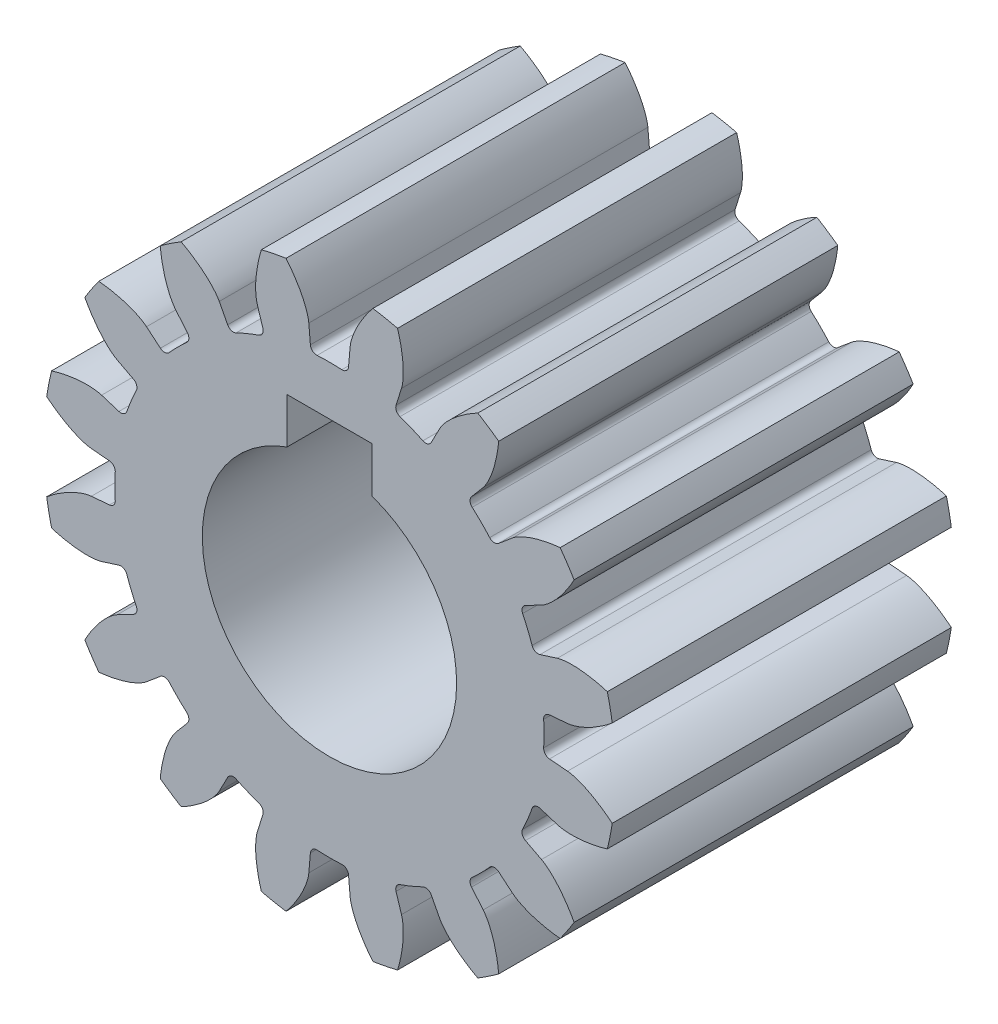
SolidWorks part; units mm, degrees
ref_plane "中间平面" through (0, 0, 0) normal (0, 0, 1) x (1, 0, 0)
ref_plane "上视基准面" through (0, 0, 0) normal (0, 1, 0) x (1, 0, 0)
ref_plane "右视基准面" through (0, 0, 0) normal (1, 0, 0) x (0, 0, -1)
sketch "直齿轮" plane through (0, 0, 0) normal (0, 0, 1) x (1, 0, 0)
  line L0 (0, 0) -> (-1.1762, 11.9422) construction
  line L2 (-0.9741, 11.2342) -> (0, 0)
  line L3 (0, 0) -> (0, 52) construction
  line L4 (1.1762, 11.9422) -> (0, 0) construction
  line L6 (0, 0) -> (0.9741, 11.2342)
  circle A0 centre (0, 0) radius 11.2763
  circle A1 centre (0, 0) radius 10.125
  arc A2 (1.1762, 11.9422) -> (-1.1762, 11.9422) centre (0, 0) ccw
  circle A3 centre (0, 0) radius 13.5
  spline S0 degree 4 poles (-0.9741, 11.2342) (-0.9778, 11.2769) (-0.9892, 11.3619) (-1.0253, 11.5213) (-1.0968, 11.7512) (-1.2514, 12.1375) (-1.5651, 12.7202) (-2.0889, 13.4422) (-2.9579, 14.3355) (-4.1214, 15.2186) (-5.5257, 15.9949) (-7.1395, 16.6146) (-8.8166, 17.0298) (-10.5294, 17.2529) (-12.3409, 17.2979) (-14.5779, 17.1195) (-17.2003, 16.566) (-20.1221, 15.4847) (-23.1427, 13.7966) (-25.8881, 11.6927) (-28.3234, 9.2384) (-30.1625, 6.8373) (-31.5207, 4.6329) (-32.5047, 2.7147) (-33.2024, 1.1373) (-33.8103, -0.4764) (-34.3283, -2.122) (-34.8638, -4.2093) (-35.2505, -6.3331) (-35.4664, -8.2594) (-35.5513, -9.8775) (-35.5719, -10.733) (-35.5755, -11.3167) (-35.5737, -11.7731) (-35.5588, -12.4198) (-35.5403, -12.9018) (-35.4983, -13.6946) (-35.4489, -14.3031) (-35.381, -15.0475) (-35.3029, -15.7061) (-35.2097, -16.417) (-35.1048, -17.0883) (-35.0154, -17.6149) (-34.9522, -17.9493) (-34.9192, -18.1231) knots 0 0 0 0 0 0.002802 0.005604 0.010661 0.015718 0.02996 0.048734 0.068727 0.096889 0.125051 0.153212 0.181374 0.209535 0.237696 0.271429 0.327752 0.384075 0.440398 0.496721 0.553044 0.609367 0.637529 0.66569 0.693852 0.722013 0.750174 0.778336 0.834659 0.86282 0.876901 0.883942 0.890982 0.900036 0.909091 0.920455 0.931818 0.943182 0.954545 0.965909 0.977273 0.988636 1 1 1 1 1 construction
  spline S1 degree 4 poles (-0.9741, 11.2342) (-0.9778, 11.2769) (-0.9892, 11.3619) (-1.0253, 11.5213) (-1.0968, 11.7512) (-1.2514, 12.1375) (-1.5651, 12.7202) (-2.0889, 13.4422) (-2.9579, 14.3355) (-4.1214, 15.2186) (-5.5257, 15.9949) (-7.1395, 16.6146) (-8.8166, 17.0298) (-10.5294, 17.2529) (-12.3409, 17.2979) (-14.5779, 17.1195) (-17.2003, 16.566) (-20.1221, 15.4847) (-23.1427, 13.7966) (-25.8881, 11.6927) (-28.3234, 9.2384) (-30.1625, 6.8373) (-31.5207, 4.6329) (-32.5047, 2.7147) (-33.2024, 1.1373) (-33.8103, -0.4764) (-34.3283, -2.122) (-34.8638, -4.2093) (-35.2505, -6.3331) (-35.4664, -8.2594) (-35.5513, -9.8775) (-35.5719, -10.733) (-35.5755, -11.3167) (-35.5737, -11.7731) (-35.5634, -12.2185) (-35.5555, -12.4735) (-35.5509, -12.5994) knots 0 0 0 0 0 0.002802 0.005604 0.010661 0.015718 0.02996 0.048734 0.068727 0.096889 0.125051 0.153212 0.181374 0.209535 0.237696 0.271429 0.327752 0.384075 0.440398 0.496721 0.553044 0.609367 0.637529 0.66569 0.693852 0.722013 0.750174 0.778336 0.834659 0.86282 0.876901 0.883942 0.890982 0.900036 0.909091 0.909091 0.909091 0.909091 0.909091
  spline S2 degree 4 poles (0.9741, 11.2342) (0.9778, 11.2769) (0.9892, 11.3619) (1.0253, 11.5213) (1.0968, 11.7512) (1.2514, 12.1375) (1.5651, 12.7202) (2.0889, 13.4422) (2.9579, 14.3355) (4.1214, 15.2186) (5.5257, 15.9949) (7.1395, 16.6146) (8.8166, 17.0298) (10.5294, 17.2529) (12.3409, 17.2979) (14.5779, 17.1195) (17.2003, 16.566) (20.1221, 15.4847) (23.1427, 13.7966) (25.8881, 11.6927) (28.3234, 9.2384) (30.1625, 6.8373) (31.5207, 4.6329) (32.5047, 2.7147) (33.2024, 1.1373) (33.8103, -0.4764) (34.3283, -2.122) (34.8638, -4.2093) (35.2505, -6.3331) (35.4664, -8.2594) (35.5513, -9.8775) (35.5719, -10.733) (35.5755, -11.3167) (35.5737, -11.7731) (35.5588, -12.4198) (35.5403, -12.9018) (35.4983, -13.6946) (35.4489, -14.3031) (35.381, -15.0475) (35.3029, -15.7061) (35.2097, -16.417) (35.1048, -17.0883) (35.0154, -17.6149) (34.9522, -17.9493) (34.9192, -18.1231) knots 0 0 0 0 0 0.002802 0.005604 0.010661 0.015718 0.02996 0.048734 0.068727 0.096889 0.125051 0.153212 0.181374 0.209535 0.237696 0.271429 0.327752 0.384075 0.440398 0.496721 0.553044 0.609367 0.637529 0.66569 0.693852 0.722013 0.750174 0.778336 0.834659 0.86282 0.876901 0.883942 0.890982 0.900036 0.909091 0.920455 0.931818 0.943182 0.954545 0.965909 0.977273 0.988636 1 1 1 1 1 construction
  spline S3 degree 4 poles (0.9741, 11.2342) (0.9778, 11.2769) (0.9892, 11.3619) (1.0253, 11.5213) (1.0968, 11.7512) (1.2514, 12.1375) (1.5651, 12.7202) (2.0889, 13.4422) (2.9579, 14.3355) (4.1214, 15.2186) (5.5257, 15.9949) (7.1395, 16.6146) (8.8166, 17.0298) (10.5294, 17.2529) (12.3409, 17.2979) (14.5779, 17.1195) (17.2003, 16.566) (20.1221, 15.4847) (23.1427, 13.7966) (25.8881, 11.6927) (28.3234, 9.2384) (30.1625, 6.8373) (31.5207, 4.6329) (32.5047, 2.7147) (33.2024, 1.1373) (33.8103, -0.4764) (34.3283, -2.122) (34.8638, -4.2093) (35.2505, -6.3331) (35.4664, -8.2594) (35.5513, -9.8775) (35.5719, -10.733) (35.5755, -11.3167) (35.5737, -11.7731) (35.5634, -12.2185) (35.5555, -12.4735) (35.5509, -12.5994) knots 0 0 0 0 0 0.002802 0.005604 0.010661 0.015718 0.02996 0.048734 0.068727 0.096889 0.125051 0.153212 0.181374 0.209535 0.237696 0.271429 0.327752 0.384075 0.440398 0.496721 0.553044 0.609367 0.637529 0.66569 0.693852 0.722013 0.750174 0.778336 0.834659 0.86282 0.876901 0.883942 0.890982 0.900036 0.909091 0.909091 0.909091 0.909091 0.909091
  dimension "基圆直径" = 22.5526
  dimension "齿根圆" = 20.25
  dimension "分度圆" = 24
  dimension "齿顶圆" = 27
  dimension "D1" = 2.3562
sketch "圆" plane through (0, 0, 0) normal (0, 0, 1) x (1, 0, 0)
  circle A0 centre (0, 0) radius 13.5 construction
  circle A1 centre (0, 0) radius 13.5
extrude "毛胚" add sketch "圆" along normal mid plane 16
chamfer "轮齿倒角" [suppressed] distance 0.001 angle 45
sketch "齿形" plane through (0, 0, 0) normal (0, 0, 1) x (1, 0, 0)
  line L4 (0, 0) -> (0.9741, 11.2342) construction
  line L5 (-0.9741, 11.2342) -> (0, 0) construction
  line L6 (0, 0) -> (0.9741, 11.2342)
  line L7 (-0.9741, 11.2342) -> (0, 0)
  circle A4 centre (0, 0) radius 10.125 construction
  circle A5 centre (0, 0) radius 13.5 construction
  circle A6 centre (0, 0) radius 10.125
  circle A7 centre (0, 0) radius 13.5
  spline S1 degree 4 poles (-998.5818, 40.6491) (42.2018, 3.5521) (1.6144, 7.6088) (0.5146, 9.8809) (1.0968, 11.7512) (1.2514, 12.1375) (1.5651, 12.7202) (2.0889, 13.4422) (2.9579, 14.3355) (4.1214, 15.2186) (5.5257, 15.9949) (7.1395, 16.6146) (8.8166, 17.0298) (10.5294, 17.2529) (12.3409, 17.2979) (14.5779, 17.1195) (17.2003, 16.566) (20.1221, 15.4847) (23.1427, 13.7966) (25.8881, 11.6927) (28.3234, 9.2384) (30.1625, 6.8373) (31.5207, 4.6329) (32.5047, 2.7147) (33.2024, 1.1373) (33.8103, -0.4764) (34.3283, -2.122) (34.8638, -4.2093) (35.2505, -6.3331) (35.4664, -8.2594) (35.5513, -9.8775) (35.5719, -10.733) (35.5755, -11.3167) (35.5671, -13.461) (35.2674, -18.4262) (36.5025, 22.7753) (-1.7629, -1011.8825) knots -0.112202 -0.112202 -0.112202 -0.112202 -0.112202 0.002802 0.005604 0.010661 0.015718 0.02996 0.048734 0.068727 0.096889 0.125051 0.153212 0.181374 0.209535 0.237696 0.271429 0.327752 0.384075 0.440398 0.496721 0.553044 0.609367 0.637529 0.66569 0.693852 0.722013 0.750174 0.778336 0.834659 0.86282 0.876901 0.883942 0.890982 0.900036 1.028138 1.028138 1.028138 1.028138 1.028138 only from (0.9741, 11.2342) to (35.5509, -12.5994) construction
  spline S3 degree 4 poles (998.5818, 40.6491) (-42.2018, 3.5521) (-1.6144, 7.6088) (-0.5146, 9.8809) (-1.0968, 11.7512) (-1.2514, 12.1375) (-1.5651, 12.7202) (-2.0889, 13.4422) (-2.9579, 14.3355) (-4.1214, 15.2186) (-5.5257, 15.9949) (-7.1395, 16.6146) (-8.8166, 17.0298) (-10.5294, 17.2529) (-12.3409, 17.2979) (-14.5779, 17.1195) (-17.2003, 16.566) (-20.1221, 15.4847) (-23.1427, 13.7966) (-25.8881, 11.6927) (-28.3234, 9.2384) (-30.1625, 6.8373) (-31.5207, 4.6329) (-32.5047, 2.7147) (-33.2024, 1.1373) (-33.8103, -0.4764) (-34.3283, -2.122) (-34.8638, -4.2093) (-35.2505, -6.3331) (-35.4664, -8.2594) (-35.5513, -9.8775) (-35.5719, -10.733) (-35.5755, -11.3167) (-35.5671, -13.461) (-35.2674, -18.4262) (-36.5025, 22.7753) (1.7629, -1011.8825) knots -0.112202 -0.112202 -0.112202 -0.112202 -0.112202 0.002802 0.005604 0.010661 0.015718 0.02996 0.048734 0.068727 0.096889 0.125051 0.153212 0.181374 0.209535 0.237696 0.271429 0.327752 0.384075 0.440398 0.496721 0.553044 0.609367 0.637529 0.66569 0.693852 0.722013 0.750174 0.778336 0.834659 0.86282 0.876901 0.883942 0.890982 0.900036 1.028138 1.028138 1.028138 1.028138 1.028138 only from (-0.9741, 11.2342) to (-35.5509, -12.5994) construction
  spline S4 degree 4 poles (0.9741, 11.2342) (0.9778, 11.2769) (0.9892, 11.3619) (1.0253, 11.5213) (1.0968, 11.7512) (1.2514, 12.1375) (1.5651, 12.7202) (2.0889, 13.4422) (2.9579, 14.3355) (4.1214, 15.2186) (5.5257, 15.9949) (7.1395, 16.6146) (8.8166, 17.0298) (10.5294, 17.2529) (12.3409, 17.2979) (14.5779, 17.1195) (17.2003, 16.566) (20.1221, 15.4847) (23.1427, 13.7966) (25.8881, 11.6927) (28.3234, 9.2384) (30.1625, 6.8373) (31.5207, 4.6329) (32.5047, 2.7147) (33.2024, 1.1373) (33.8103, -0.4764) (34.3283, -2.122) (34.8638, -4.2093) (35.2505, -6.3331) (35.4664, -8.2594) (35.5513, -9.8775) (35.5719, -10.733) (35.5755, -11.3167) (35.5737, -11.7731) (35.5634, -12.2185) (35.5555, -12.4735) (35.5509, -12.5994) knots 0 0 0 0 0 0.002802 0.005604 0.010661 0.015718 0.02996 0.048734 0.068727 0.096889 0.125051 0.153212 0.181374 0.209535 0.237696 0.271429 0.327752 0.384075 0.440398 0.496721 0.553044 0.609367 0.637529 0.66569 0.693852 0.722013 0.750174 0.778336 0.834659 0.86282 0.876901 0.883942 0.890982 0.900036 0.909091 0.909091 0.909091 0.909091 0.909091
  spline S5 degree 4 poles (-0.9741, 11.2342) (-0.9778, 11.2769) (-0.9892, 11.3619) (-1.0253, 11.5213) (-1.0968, 11.7512) (-1.2514, 12.1375) (-1.5651, 12.7202) (-2.0889, 13.4422) (-2.9579, 14.3355) (-4.1214, 15.2186) (-5.5257, 15.9949) (-7.1395, 16.6146) (-8.8166, 17.0298) (-10.5294, 17.2529) (-12.3409, 17.2979) (-14.5779, 17.1195) (-17.2003, 16.566) (-20.1221, 15.4847) (-23.1427, 13.7966) (-25.8881, 11.6927) (-28.3234, 9.2384) (-30.1625, 6.8373) (-31.5207, 4.6329) (-32.5047, 2.7147) (-33.2024, 1.1373) (-33.8103, -0.4764) (-34.3283, -2.122) (-34.8638, -4.2093) (-35.2505, -6.3331) (-35.4664, -8.2594) (-35.5513, -9.8775) (-35.5719, -10.733) (-35.5755, -11.3167) (-35.5737, -11.7731) (-35.5634, -12.2185) (-35.5555, -12.4735) (-35.5509, -12.5994) knots 0 0 0 0 0 0.002802 0.005604 0.010661 0.015718 0.02996 0.048734 0.068727 0.096889 0.125051 0.153212 0.181374 0.209535 0.237696 0.271429 0.327752 0.384075 0.440398 0.496721 0.553044 0.609367 0.637529 0.66569 0.693852 0.722013 0.750174 0.778336 0.834659 0.86282 0.876901 0.883942 0.890982 0.900036 0.909091 0.909091 0.909091 0.909091 0.909091
extrude "插齿" cut sketch "齿形" against normal mid plane 16 contours S5 A6 S4 A7
fillet "圆角1" [suppressed] radius 0.3
pattern_circular "圆周阵列1" [suppressed] count 16 over 360
fillet "圆角2" radius 0.3 2 edges at (0.8747, 10.0871, 0) (-0.8747, 10.0871, 0)
pattern_circular "圆周阵列2" count 16 over 360 about axis through (0, 0, 8) along (0, 0, -1) of "圆角2", "插齿"
sketch "分度圆" plane through (0, 0, 0) normal (0, 0, 1) x (1, 0, 0)
  circle A0 centre (0, 0) radius 12 construction
  circle A1 centre (0, 0) radius 12 construction
sketch "草图1" plane through (0, 0, 8) normal (0, 0, 1) x (1, 0, 0)
  line L0 (0, 6) -> (2, 4.2) construction
  line L1 (-2, 4.2) -> (2, 4.2) construction
  line L2 (-2, 5.6569) -> (-2, 7.8)
  line L3 (-2, 7.8) -> (2, 7.8)
  line L4 (2, 5.6569) -> (2, 7.8)
  line L5 (0, 6) -> (2, 7.8) construction
  line L6 (-2, 7.8) -> (0, 6) construction
  line L7 (2, 4.2) -> (2, 5.6569) construction
  line L8 (-2, 4.2) -> (0, 6) construction
  line L9 (-2, 4.2) -> (-2, 5.6569) construction
  arc A0 (-2, 5.6569) -> (2, 5.6569) centre (0, 0) ccw
  arc A1 (2, 5.6569) -> (0, 6) centre (0, 0) ccw construction
  arc A2 (0, 6) -> (-2, 5.6569) centre (0, 0) ccw construction
  point P3 (0, 6)
  dimension "D1" = 12
  dimension "D2" = 13.8
  dimension "D3" = 4
extrude "切除-拉伸1" cut sketch "草图1" against normal through all both and the other way through all
equation "\"m\" = 1.5'模数"
equation "\"z\" = 16'齿数"
equation "\"a\" = 20'压力角（常见为20°）"
equation "\"B\"= 16'齿宽"
equation "\"C1\" = 0'轮齿倒角（若设为0，则无倒角）"
equation "\"x\"= 0'变位系数（不懂勿动）"
equation "\"ha\"= 1'齿顶高系数（不懂勿动）"
equation "\"c\"= 0.25'顶隙系数（不懂勿动）"
equation "\"基圆直径@直齿轮\"= \"m\" * \"z\" * cos ( \"a\" )"
equation "\"齿根圆@直齿轮\" = \"m\" * ( \"z\" - 2 * ( \"ha\" - \"x\" + \"c\" ) )"
equation "\"分度圆@直齿轮\"=\"m\" * \"z\""
equation "\"齿顶圆@直齿轮\" = \"m\" * ( \"z\" + 2 * ( \"ha\" + \"x\" ) )"
equation "\"R\"= 0.3'齿根圆角"
equation "\"D1\"= \"R\""
equation "\"D1@毛胚\" = \"B\""
equation "\"D1@轮齿倒角\" = IIF ( \"C1\" > 0 , \"C1\" , 0.001 )"
equation "\"轮齿倒角\"= IIF ( \"C1\" > 0 , \"unsuppressed\" , \"suppressed\" )"
equation "\"D1@插齿\" = \"B\""
equation "\"D1@圆周阵列1\" = \"z\""
equation "\"D1@直齿轮\"= \"m\" * ( pi / 2 ) - 2 * \"m\" * tan ( \"a\" ) * \"x\"'作者：机械菌-"
equation "\"D1@圆角1\"=\"R\""
equation "\"圆角1\" = IIF ( \"m\" * ( \"z\" - 2 * ( \"ha\" - \"x\" + \"c\" ) ) > \"m\" * \"z\" * cos ( \"a\" ) , \"unsuppressed\" , \"suppressed\" )"
equation "\"圆周阵列1\"= IIF ( \"m\" * ( \"z\" - 2 * ( \"ha\" - \"x\" + \"c\" ) ) > \"m\" * \"z\" * cos ( \"a\" ) , \"unsuppressed\" , \"suppressed\" )"
equation "\"D1@圆角2\"=\"R\""
equation "\"D1@圆周阵列2\" = \"z\""
equation "\"圆角2\" = IIF ( \"m\" * ( \"z\" - 2 * ( \"ha\" - \"x\" + \"c\" ) ) < \"m\" * \"z\" * cos ( \"a\" ) , \"unsuppressed\" , \"suppressed\" )"
equation "\"圆周阵列2\"= IIF ( \"m\" *  ( \"z\" - 2 *  ( \"ha\" - \"x\" + \"c\" )  )  < \"m\" * \"z\" * cos ( \"a\" )  ,  unsuppressed  ,  suppressed  ) "
